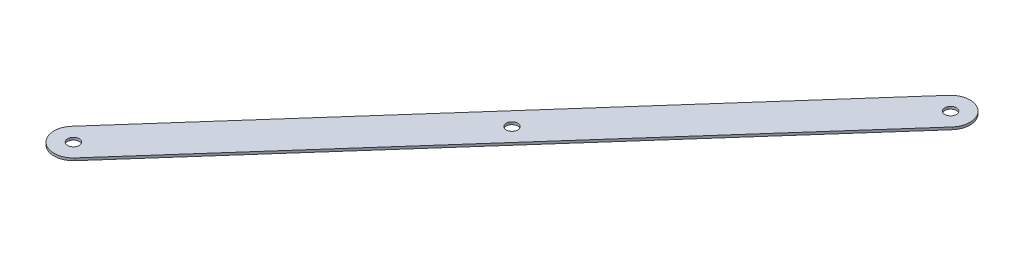
SolidWorks part; units mm, degrees
ref_plane "Front" through (0, 0, 0) normal (0, 0, 1) x (1, 0, 0)
ref_plane "Top" through (0, 0, 0) normal (0, 1, 0) x (1, 0, 0)
ref_plane "Right" through (0, 0, 0) normal (1, 0, 0) x (0, 0, -1)
sketch "Sketch1" plane through (0, 0, 0) normal (0, 1, 0) x (1, 0, 0)
  line L0 (0, 0) -> (269.2956, 304.3695) construction
  line L1 (-9.5115, 8.4155) -> (259.7841, 312.785)
  line L2 (9.5115, -8.4155) -> (278.8072, 295.9541)
  arc A0 (-9.5115, 8.4155) -> (9.5115, -8.4155) centre (0, 0) ccw
  arc A1 (278.8072, 295.9541) -> (259.7841, 312.785) centre (269.2956, 304.3695) ccw
  circle A2 centre (134.6478, 152.1848) radius 3.81
  circle A3 centre (269.2956, 304.3695) radius 3.81
  circle A4 centre (0, 0) radius 3.81
  point P3 (134.6478, 152.1848)
  dimension "D3" = 7.62
  dimension "D4" = 7.62
  dimension "D5" = 7.62
  dimension "D1" = 406.4
  dimension "D2" = 25.4
extrude "Boss-Extrude1" add sketch "Sketch1" along normal blind 1.5875
